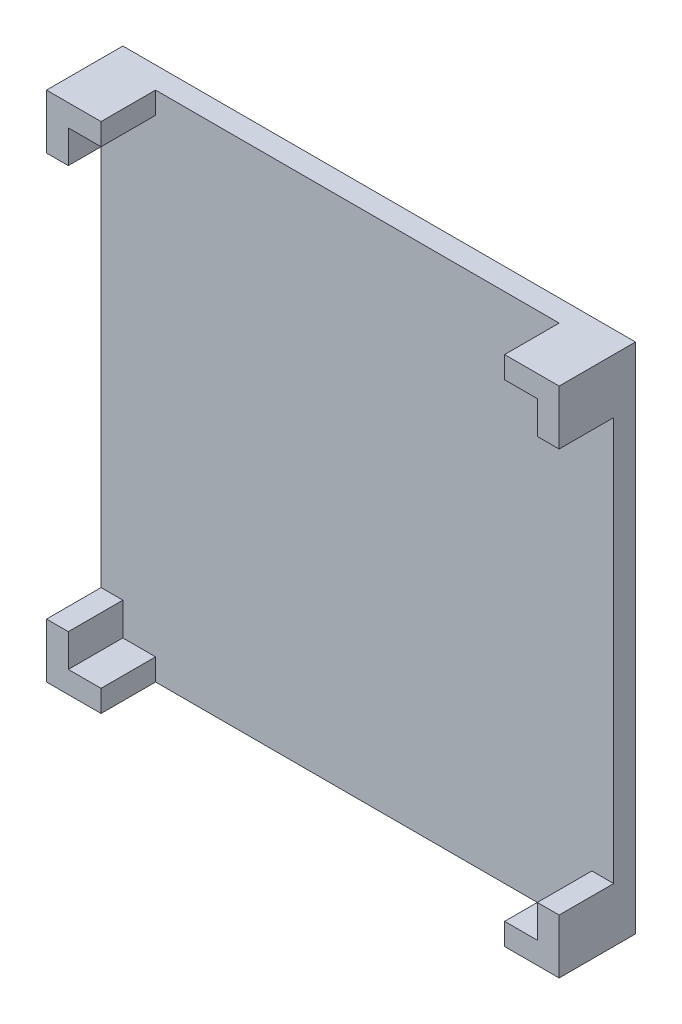
SolidWorks part; units mm, degrees
ref_plane "Front Plane" through (0, 0, 0) normal (0, 0, 1) x (1, 0, 0)
ref_plane "Top Plane" through (0, 0, 0) normal (0, 1, 0) x (1, 0, 0)
ref_plane "Right Plane" through (0, 0, 0) normal (1, 0, 0) x (0, 0, -1)
sketch "Sketch1" plane through (0, 0, 0) normal (0, 0, 1) x (1, 0, 0)
  line L0 (0, 0) -> (47, 0)
  line L1 (47, 0) -> (47, 47)
  line L2 (47, 47) -> (0, 47)
  line L3 (0, 47) -> (0, 0)
  dimension "D1" = 47
  dimension "D2" = 47
extrude "Boss-Extrude1" add sketch "Sketch1" along normal blind 2
sketch "Sketch2" plane through (0, 0, 2) normal (0, 0, 1) x (1, 0, 0)
  line L0 (5, 47) -> (5, 45)
  line L1 (47, 47) -> (0, 47) construction
  line L2 (5, 45) -> (2, 45)
  line L3 (2, 45) -> (2, 42)
  line L4 (2, 42) -> (0, 42)
  line L5 (0, 47) -> (0, 0) construction
  line L6 (0, 42) -> (0, 47)
  line L7 (0, 47) -> (5, 47)
  line L8 (42, 47) -> (42, 45)
  line L9 (42, 45) -> (45, 45)
  line L10 (45, 45) -> (45, 42)
  line L11 (45, 42) -> (47, 42)
  line L12 (47, 0) -> (47, 47) construction
  line L13 (47, 42) -> (47, 47)
  line L14 (47, 47) -> (42, 47)
  line L15 (0, 5) -> (0, 0)
  line L16 (0, 0) -> (5, 0)
  line L17 (0, 0) -> (47, 0) construction
  line L18 (5, 0) -> (5, 2)
  line L19 (5, 2) -> (2, 2)
  line L20 (2, 2) -> (2, 5)
  line L21 (2, 5) -> (0, 5)
  line L22 (47, 5) -> (45, 5)
  line L23 (45, 5) -> (45, 2)
  line L24 (45, 2) -> (42, 2)
  line L25 (42, 2) -> (42, 0)
  line L26 (42, 0) -> (47, 0)
  line L27 (47, 0) -> (47, 5)
  dimension "D1" = 5
  dimension "D2" = 5
  dimension "D3" = 3
  dimension "D4" = 3
  dimension "D5" = 5
  dimension "D6" = 5
  dimension "D7" = 3
  dimension "D8" = 3
  dimension "D9" = 5
  dimension "D10" = 5
  dimension "D11" = 3
  dimension "D12" = 3
  dimension "D13" = 5
  dimension "D14" = 3
  dimension "D15" = 3
extrude "Boss-Extrude2" add sketch "Sketch2" along normal blind 5
